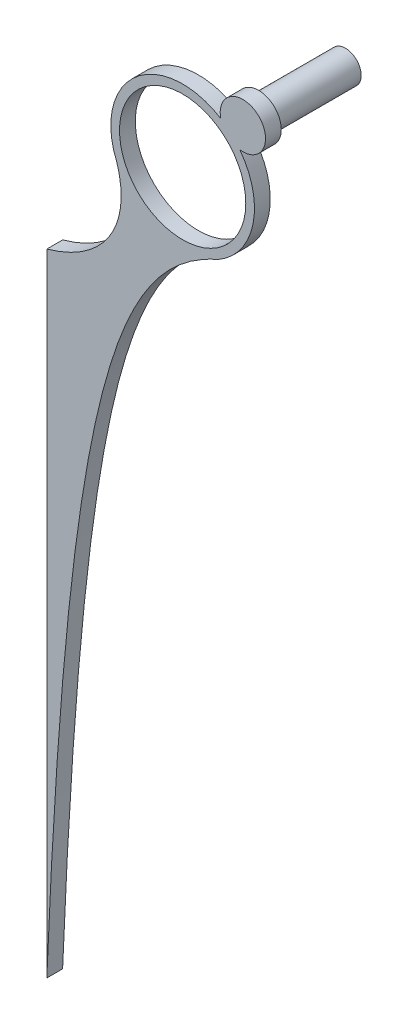
SolidWorks part; units mm, degrees
material "1060 合金"
ref_plane "前视基准面" through (0, 0, 0) normal (0, 0, 1) x (1, 0, 0)
ref_plane "上视基准面" through (0, 0, 0) normal (0, 1, 0) x (1, 0, 0)
ref_plane "右视基准面" through (0, 0, 0) normal (1, 0, 0) x (0, 0, -1)
other "Configuration Table"
sketch "草图1" plane through (0, 0, 0) normal (0, 0, 1) x (1, 0, 0)
  line L1 (0, 0) -> (0, -80)
  circle A0 centre (17.2116, 17.6209) radius 8
  circle A1 centre (17.2116, 17.6209) radius 9.1022
  spline S0 degree 3 poles (0, 0) (7.6191, 2.1521) (10.8357, 7.8832) (8.845, 14.0361) knots 0 0 0 0 1 1 1 1
  spline S1 degree 3 poles (0, -80) (2.7677, -12.9825) (8.8482, 4.1197) (21.7058, 9.7055) knots 0 0 0 0 1 1 1 1
extrude "凸台-拉伸1" add sketch "草图1" along normal blind 2 contours L1 S1 A1 S0 | A1 S1 S0 A0
sketch "草图4" plane through (0, 0, 0) normal (0, 0, -1) x (-1, 0, 0)
  circle A0 centre (-24.8403, 25.9645) radius 2
  point P2 (-23.6266, 26.2472)
  point P3 (0, 0)
extrude "凸台-拉伸3" add sketch "草图4" along normal blind 11
sketch "草图5" plane through (0, 0, 0) normal (0, 0, -1) x (-1, 0, 0)
  circle A1 centre (-24.8403, 25.9645) radius 2.8709
  point P1 (0, 0)
extrude "凸台-拉伸4" add sketch "草图5" against normal blind 2
